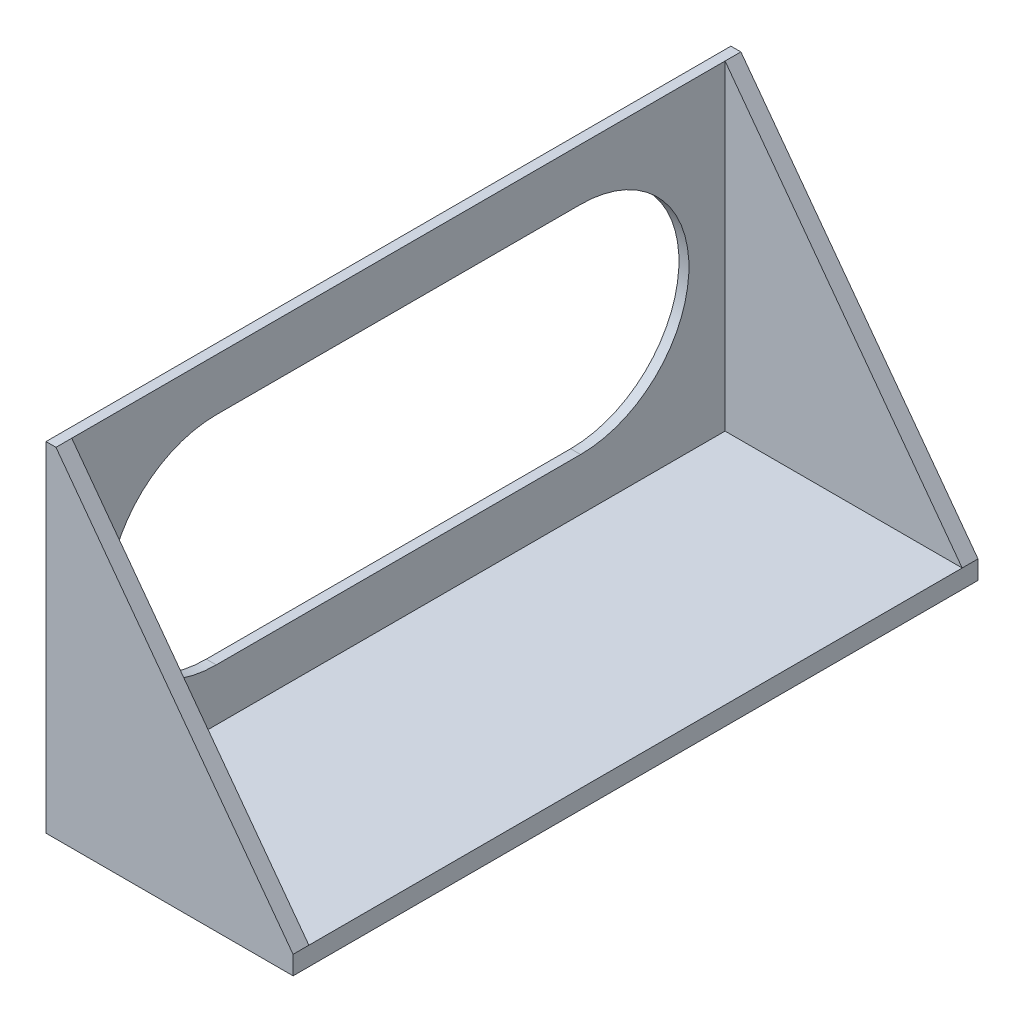
SolidWorks part; units mm, degrees
ref_plane "Front" through (0, 0, 0) normal (0, 0, 1) x (1, 0, 0)
ref_plane "Top" through (0, 0, 0) normal (0, 1, 0) x (1, 0, 0)
ref_plane "Right" through (0, 0, 0) normal (1, 0, 0) x (0, 0, -1)
sketch "Sketch2" plane through (0, 0, 0) normal (0, 1, 0) x (1, 0, 0)
  line L0 (0, -155.702) -> (0, 155.702)
  line L1 (-155.702, -155.702) -> (155.702, -155.702)
  line L2 (-155.702, -155.702) -> (-155.702, 155.702)
  line L3 (-155.702, 155.702) -> (155.702, 155.702)
  line L4 (155.702, -155.702) -> (155.702, 155.702)
  line L9 (-155.702, 0) -> (155.702, 0)
  line L11 (-152.4, 152.4) -> (152.4, 152.4)
  line L12 (-152.4, 152.4) -> (-152.4, -152.4)
  line L13 (-152.4, -152.4) -> (152.4, -152.4)
  line L14 (152.4, 152.4) -> (152.4, -152.4)
  line L15 (-152.4, 152.4) -> (152.4, -152.4) construction
  line L16 (-152.4, -152.4) -> (152.4, 152.4) construction
  line L17 (-149.098, 149.098) -> (149.098, 149.098)
  line L18 (-149.098, 149.098) -> (-149.098, -149.098)
  line L19 (-149.098, -149.098) -> (149.098, -149.098)
  line L20 (149.098, 149.098) -> (149.098, -149.098)
  line L21 (-149.098, 149.098) -> (149.098, -149.098) construction
  line L22 (-149.098, -149.098) -> (149.098, 149.098) construction
  line L23 (-144.78, 144.78) -> (144.78, 144.78)
  line L24 (-144.78, 144.78) -> (-144.78, -144.78)
  line L25 (-144.78, -144.78) -> (144.78, -144.78)
  line L26 (144.78, 144.78) -> (144.78, -144.78)
  line L27 (-144.78, 144.78) -> (144.78, -144.78) construction
  line L28 (-144.78, -144.78) -> (144.78, 144.78) construction
  line L29 (-136.652, -136.652) -> (136.652, -136.652)
  line L30 (-136.652, -136.652) -> (-136.652, 136.652)
  line L31 (-136.652, 136.652) -> (136.652, 136.652)
  line L32 (136.652, -136.652) -> (136.652, 136.652)
  line L33 (-136.652, -136.652) -> (136.652, 136.652) construction
  line L34 (-136.652, 136.652) -> (136.652, -136.652) construction
  point P8 (0, 0)
  point P13 (0, 0)
  point P18 (0, 0)
  point P25 (0, 0)
  dimension "D1" = 311.404
  dimension "D2" = 3.302
  dimension "D3" = 3.302
  dimension "D4" = 4.318
  dimension "D5" = 273.304
  dimension "D6" = 289.56
extrude "Boss-Extrude1" add sketch "Sketch2" along normal blind 67.31 contours L1 L4 L3 L2
sketch "Sketch4" plane through (0, 67.31, 0) normal (0, 1, 0) x (1, 0, 0)
  line L0 (-144.78, -144.78) -> (144.78, -144.78) construction
  line L1 (144.78, 144.78) -> (144.78, -144.78) construction
  line L2 (-144.78, 144.78) -> (144.78, 144.78) construction
  line L3 (-144.78, 144.78) -> (-144.78, -144.78) construction
  line L4 (-144.78, -144.78) -> (144.78, -144.78)
  line L5 (144.78, 144.78) -> (144.78, -144.78)
  line L6 (-144.78, 144.78) -> (144.78, 144.78)
  line L7 (-144.78, 144.78) -> (-144.78, -144.78)
extrude "Cut-Extrude1" cut sketch "Sketch4" against normal blind 25.4
sketch "Sketch5" plane through (0, 67.31, 0) normal (0, 1, 0) x (1, 0, 0)
  line L0 (-136.652, -136.652) -> (136.652, -136.652) construction
  line L1 (136.652, -136.652) -> (136.652, 136.652) construction
  line L2 (-136.652, 136.652) -> (136.652, 136.652) construction
  line L3 (-136.652, -136.652) -> (-136.652, 136.652) construction
  line L4 (-136.652, -136.652) -> (136.652, -136.652)
  line L5 (136.652, -136.652) -> (136.652, 136.652)
  line L6 (-136.652, 136.652) -> (136.652, 136.652)
  line L7 (-136.652, -136.652) -> (-136.652, 136.652)
extrude "Cut-Extrude2" cut sketch "Sketch5" against normal blind 60.96
sketch "Sketch6" plane through (0, 67.31, 0) normal (0, 1, 0) x (1, 0, 0)
  line L0 (-152.4, -152.4) -> (152.4, -152.4) construction
  line L1 (-149.098, -149.098) -> (149.098, -149.098) construction
  line L2 (152.4, 152.4) -> (152.4, -152.4) construction
  line L3 (149.098, 149.098) -> (149.098, -149.098) construction
  line L4 (-149.098, 149.098) -> (149.098, 149.098) construction
  line L5 (-152.4, 152.4) -> (152.4, 152.4) construction
  line L6 (-152.4, 152.4) -> (-152.4, -152.4) construction
  line L7 (-149.098, 149.098) -> (-149.098, -149.098) construction
  line L8 (-152.4, -152.4) -> (152.4, -152.4)
  line L9 (-149.098, -149.098) -> (149.098, -149.098)
  line L10 (152.4, 152.4) -> (152.4, -152.4)
  line L11 (149.098, 149.098) -> (149.098, -149.098)
  line L12 (-149.098, 149.098) -> (149.098, 149.098)
  line L13 (-152.4, 152.4) -> (152.4, 152.4)
  line L14 (-152.4, 152.4) -> (-152.4, -152.4)
  line L15 (-149.098, 149.098) -> (-149.098, -149.098)
extrude "Cut-Extrude3" cut sketch "Sketch6" against normal blind 12.7
sketch "Sketch7" plane through (-155.702, 0, 0) normal (-1, 0, 0) x (0, 0, 1)
  line L0 (-29.275, 25.75) -> (29.275, 25.75) construction
  line L1 (-29.275, 43.15) -> (29.275, 43.15)
  line L2 (-29.275, 8.35) -> (29.275, 8.35)
  line L3 (-46.675, 25.75) -> (46.675, 25.75) construction
  line L4 (136.652, 6.35) -> (-136.652, 6.35) construction
  arc A0 (-29.275, 43.15) -> (-29.275, 8.35) centre (-29.275, 25.75) ccw
  arc A1 (29.275, 8.35) -> (29.275, 43.15) centre (29.275, 25.75) ccw
  point P2 (0, 25.75)
  dimension "D1" = 34.8
  dimension "D2" = 93.35
  dimension "D3" = 2
extrude "Cut-Extrude4" cut sketch "Sketch7" against normal up to next
sketch "Sketch8" plane through (-136.652, 0, 0) normal (1, 0, 0) x (0, 0, -1)
  line L6 (29.275, 45.15) -> (48.675, 45.15)
  line L7 (48.675, 45.15) -> (48.675, 25.75)
  line L8 (-29.275, 6.35) -> (29.275, 6.35)
  line L9 (29.275, 45.15) -> (-29.275, 45.15)
  line L10 (-29.275, 6.35) -> (29.275, 6.35)
  line L11 (29.275, 45.15) -> (-29.275, 45.15)
  line L12 (48.675, 25.75) -> (48.675, 6.35)
  line L13 (48.675, 6.35) -> (29.275, 6.35)
  line L14 (-29.275, 45.15) -> (-48.675, 45.15)
  line L15 (-48.675, 45.15) -> (-48.675, 25.75)
  line L16 (-48.675, 25.75) -> (-48.675, 6.35)
  line L17 (-48.675, 6.35) -> (-29.275, 6.35)
  arc A9 (-29.275, 45.15) -> (-29.275, 6.35) centre (-29.275, 25.75) ccw
  arc A10 (29.275, 6.35) -> (29.275, 45.15) centre (29.275, 25.75) ccw
  arc A11 (-29.275, 45.15) -> (-29.275, 6.35) centre (-29.275, 25.75) ccw construction
  arc A12 (29.275, 6.35) -> (29.275, 45.15) centre (29.275, 25.75) ccw construction
  dimension "D1" = 2
extrude "Cut-Extrude5" cut sketch "Sketch8" against normal offset from surface (17.45 mm away) 1.6 up to face at (-155.702, 25.75, 0)
sketch "Sketch9" plane through (-155.702, 0, 0) normal (-1, 0, 0) x (0, 0, 1)
  line L5 (46.0141, 30.5) -> (48.175, 30.5)
  line L7 (46.0141, 21) -> (48.175, 21)
  line L8 (48.175, 30.5) -> (48.175, 21)
  arc A1 (29.275, 8.35) -> (29.275, 43.15) centre (29.275, 25.75) ccw construction
  arc A2 (29.275, 8.35) -> (29.275, 43.15) centre (29.275, 25.75) ccw construction
  arc A3 (46.0141, 30.5) -> (46.0141, 21) centre (29.275, 25.75) cw
  point P8 (46.675, 25.75)
  point P13 (48.175, 25.75)
  dimension "D1" = 1.5
  dimension "D2" = 9.5
extrude "Cut-Extrude6" cut sketch "Sketch9" against normal up to next
sketch "Sketch11" plane through (-136.652, 0, 0) normal (1, 0, 0) x (0, 0, -1)
  line L0 (-48.675, 41.91) -> (-48.675, 6.35) construction
  line L1 (-48.675, 35.56) -> (-124.875, 35.56)
  line L2 (-48.675, 35.56) -> (-48.675, 15.24)
  line L3 (-48.675, 15.24) -> (-124.875, 15.24)
  line L4 (-124.875, 35.56) -> (-124.875, 15.24)
  line L5 (-48.675, 41.91) -> (-144.78, 41.91) construction
  dimension "D1" = 6.35
  dimension "D2" = 76.2
  dimension "D3" = 20.32
extrude "Cut-Extrude7" cut sketch "Sketch11" against normal up to surface (17.45 mm away) up to face at (-154.102, 25.75, 0)
sketch "Sketch12" plane through (-154.102, 0, 0) normal (1, 0, 0) x (0, 0, -1)
  line L0 (-48.675, 35.56) -> (-48.675, 15.24)
  line L8 (-48.675, 6.35) -> (48.675, 6.35)
  line L9 (48.675, 6.35) -> (48.675, 45.15)
  line L10 (48.675, 45.15) -> (-48.675, 45.15)
  line L11 (-48.675, 45.15) -> (-48.675, 35.56)
  line L12 (-48.675, 35.56) -> (-124.875, 35.56)
  line L13 (-124.875, 35.56) -> (-124.875, 15.24)
  line L14 (-124.875, 15.24) -> (-48.675, 15.24)
  line L15 (-48.675, 15.24) -> (-48.675, 6.35)
  line L16 (-48.675, 6.35) -> (48.675, 6.35)
  line L17 (48.675, 6.35) -> (48.675, 45.15)
  line L18 (48.675, 45.15) -> (-48.675, 45.15)
  line L19 (-48.675, 45.15) -> (-48.675, 35.56)
  line L23 (-48.675, 15.24) -> (-48.675, 6.35)
  dimension "D1" = 0
extrude "Cut-Extrude8" cut sketch "Sketch12" against normal through all both and the other way through all flip side to cut
sketch "Sketch13" plane through (-154.102, 0, 0) normal (1, 0, 0) x (0, 0, -1)
  line L0 (55.025, 51.5) -> (-55.025, 51.5)
  line L1 (-55.025, 51.5) -> (-55.025, 0)
  line L2 (-55.025, 0) -> (55.025, 0)
  line L3 (55.025, 0) -> (55.025, 51.5)
  line L4 (48.675, 45.15) -> (-48.675, 45.15)
  line L5 (-48.675, 45.15) -> (-48.675, 6.35)
  line L6 (-48.675, 6.35) -> (48.675, 6.35)
  line L7 (48.675, 6.35) -> (48.675, 45.15)
  line L8 (48.675, 45.15) -> (-48.675, 45.15)
  line L9 (-48.675, 45.15) -> (-48.675, 6.35)
  line L10 (-48.675, 6.35) -> (48.675, 6.35)
  line L11 (48.675, 6.35) -> (48.675, 45.15)
  dimension "D1" = 0
  dimension "D2" = 6.35
extrude "Boss-Extrude2" add sketch "Sketch13" against normal up to surface (1.6 mm away) up to face at (-155.702, 25.75, 21.9026)
sketch "Sketch15" plane through (-154.102, 0, 0) normal (1, 0, 0) x (0, 0, -1)
  line L0 (55.025, 0) -> (55.025, 51.5) construction
  line L1 (-55.025, 0) -> (55.025, 0)
  line L2 (-55.025, 0) -> (-55.025, -3)
  line L3 (-55.025, -3) -> (55.025, -3)
  line L4 (55.025, 0) -> (55.025, -3)
  dimension "D1" = 3
extrude "Boss-Extrude3" add sketch "Sketch15" along normal blind 38.1 and the other way up to surface (1.6 mm away) other way up to face at (-155.702, 25.75, 21.9026)
sketch "Sketch16" plane through (0, 0, 55.025) normal (0, 0, 1) x (1, 0, 0)
  line L0 (-154.102, 51.5) -> (-116.002, 0)
  line L1 (-154.102, 0) -> (-116.002, 0) construction
  point P5 (-116.002, 0)
rib "Rib1" sketch "Sketch16" sketch "Sketch16" thickness 2.54 extrusion direction parallel to sketch draft on no parameters "D1"=2.54
mirror "Mirror1" about plane through (0, 0, 0) normal (0, 0, 1) of "Rib1"
